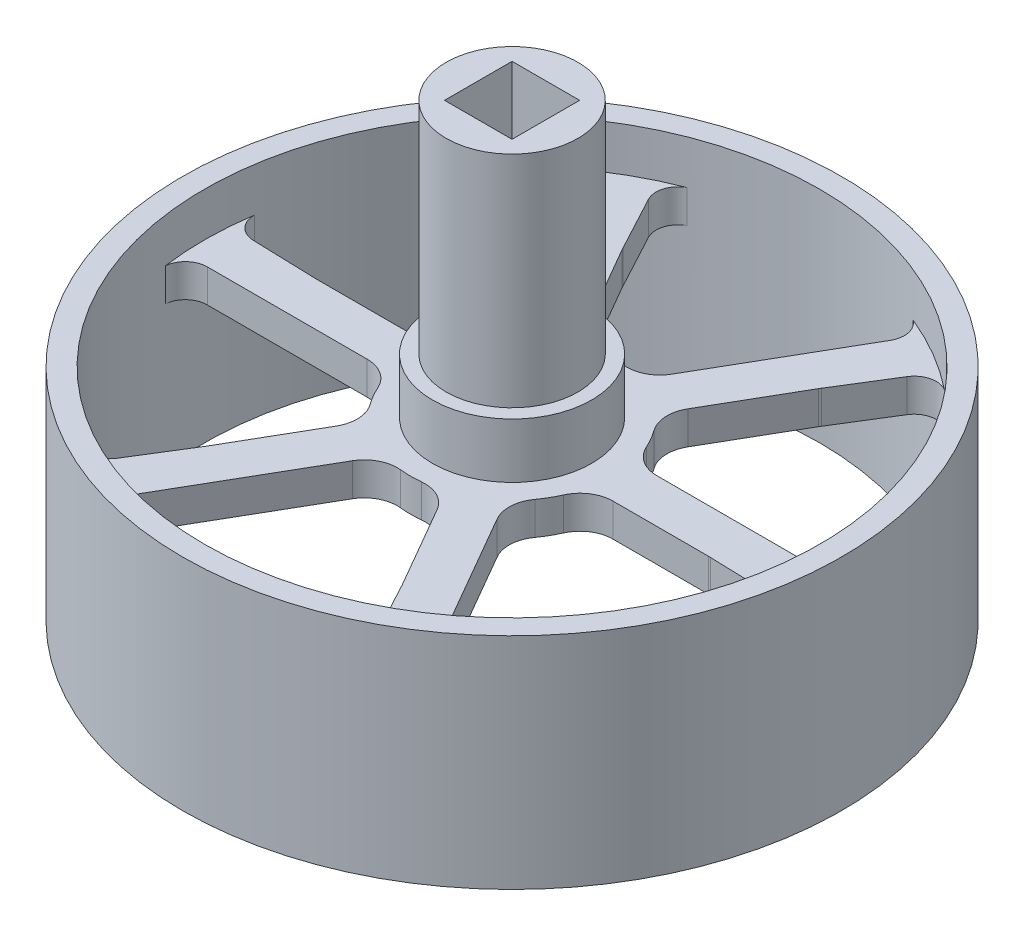
SolidWorks part; units mm, degrees
ref_plane "Front Plane" through (0, 0, 0) normal (0, 0, 1) x (1, 0, 0)
ref_plane "Top Plane" through (0, 0, 0) normal (0, 1, 0) x (1, 0, 0)
ref_plane "Right Plane" through (0, 0, 0) normal (1, 0, 0) x (0, 0, -1)
sketch "Sketch1" plane through (0, 0, 0) normal (0, 1, 0) x (1, 0, 0)
  circle A0 centre (0, 0) radius 30
  circle A1 centre (0, 0) radius 28
  dimension "D1" = 60
  dimension "D2" = 2
extrude "Boss-Extrude1" add sketch "Sketch1" along normal mid plane 20
sketch "Sketch2" plane through (0, 0, 0) normal (0, 1, 0) x (1, 0, 0)
  circle A0 centre (0, 0) radius 28
  circle A1 centre (0, 0) radius 28 construction
extrude "Boss-Extrude2" add sketch "Sketch2" along normal blind 3 from offset 3
sketch "Sketch3" plane through (0, 3, 0) normal (0, -1, 0) x (1, 0, 0)
  circle A0 centre (0, 0) radius 7.25
  dimension "D1" = 14.5
extrude "Boss-Extrude3" add sketch "Sketch3" against normal blind 5 from surface at -3 starting at face at (0, 6, 28)
sketch "Sketch4" plane through (0, 11, 0) normal (0, 1, 0) x (-1, 0, 0)
  circle A0 centre (0, 0) radius 6
  dimension "D1" = 12
extrude "Boss-Extrude4" add sketch "Sketch4" along normal blind 20
sketch "Sketch6" plane through (0, 3, 0) normal (0, -1, 0) x (1, 0, 0)
  line L0 (-3.625, 6.2787) -> (-12.75, 22.0836) construction
  line L1 (3.625, 6.2787) -> (12.75, 22.0836) construction
  line L2 (0, 7.25) -> (0, 4.04) construction
  line L3 (-3.625, 6.2787) -> (0, 0) construction
  line L4 (-3.8595, 10.6849) -> (-8.2084, 18.2174)
  line L5 (3.8595, 10.6849) -> (8.2084, 18.2174)
  line L6 (-2.7835, 8.8212) -> (-9.9753, 21.2778) construction
  line L7 (2.7835, 8.8212) -> (9.9753, 21.2778) construction
  line L8 (7.3236, 8.6849) -> (11.6725, 16.2174)
  line L9 (11.1831, 2) -> (19.8809, 2)
  line L10 (11.1831, -2) -> (19.8809, -2)
  line L11 (7.3236, -8.6849) -> (11.6725, -16.2174)
  line L12 (3.8595, -10.6849) -> (8.2084, -18.2174)
  line L13 (-3.8595, -10.6849) -> (-8.2084, -18.2174)
  line L14 (-7.3236, -8.6849) -> (-11.6725, -16.2174)
  line L15 (-11.1831, -2) -> (-19.8809, -2)
  line L16 (-11.1831, 2) -> (-19.8809, 2)
  line L17 (-7.3236, 8.6849) -> (-11.6725, 16.2174)
  circle A0 centre (0, 0) radius 7.25 construction
  circle A1 centre (0, 0) radius 28
  arc A3 (3.625, 6.2787) -> (-3.625, 6.2787) centre (0, 0) ccw construction
  circle A4 centre (0, 0) radius 7.25 construction
  arc A5 (6.4313, 22.6028) -> (-6.4313, 22.6028) centre (0, 0) ccw
  arc A6 (0.9525, 9.2008) -> (-0.9525, 9.2008) centre (0, 0) ccw
  arc A7 (2.7835, 8.8212) -> (-2.7835, 8.8212) centre (0, 0) ccw construction
  arc A8 (-3.8595, 10.6849) -> (-0.9525, 9.2008) centre (-1.2614, 12.1849) ccw
  arc A9 (0.9525, 9.2008) -> (3.8595, 10.6849) centre (1.2614, 12.1849) ccw
  arc A10 (9.9753, 21.2778) -> (-9.9753, 21.2778) centre (0, 0) ccw construction
  arc A11 (6.4313, 22.6028) -> (8.2084, 18.2174) centre (5.6103, 19.7174) cw
  arc A12 (-6.4313, 22.6028) -> (-8.2084, 18.2174) centre (-5.6103, 19.7174) ccw
  arc A13 (22.7903, 5.7317) -> (16.359, 16.8711) centre (0, 0) ccw
  arc A14 (16.359, 16.8711) -> (11.6725, 16.2174) centre (14.2706, 14.7174) ccw
  arc A15 (22.7903, 5.7317) -> (19.8809, 2) centre (19.8809, 5) cw
  arc A16 (7.3236, 8.6849) -> (7.4919, 5.4253) centre (9.9217, 7.1849) ccw
  arc A17 (8.4444, 3.7755) -> (7.4919, 5.4253) centre (0, 0) ccw
  arc A18 (8.4444, 3.7755) -> (11.1831, 2) centre (11.1831, 5) ccw
  arc A19 (16.359, -16.8711) -> (22.7903, -5.7317) centre (0, 0) ccw
  arc A20 (22.7903, -5.7317) -> (19.8809, -2) centre (19.8809, -5) ccw
  arc A21 (16.359, -16.8711) -> (11.6725, -16.2174) centre (14.2706, -14.7174) cw
  arc A22 (11.1831, -2) -> (8.4444, -3.7755) centre (11.1831, -5) ccw
  arc A23 (7.4919, -5.4253) -> (8.4444, -3.7755) centre (0, 0) ccw
  arc A24 (7.4919, -5.4253) -> (7.3236, -8.6849) centre (9.9217, -7.1849) ccw
  arc A25 (-6.4313, -22.6028) -> (6.4313, -22.6028) centre (0, 0) ccw
  arc A26 (6.4313, -22.6028) -> (8.2084, -18.2174) centre (5.6103, -19.7174) ccw
  arc A27 (-6.4313, -22.6028) -> (-8.2084, -18.2174) centre (-5.6103, -19.7174) cw
  arc A28 (3.8595, -10.6849) -> (0.9525, -9.2008) centre (1.2614, -12.1849) ccw
  arc A29 (-0.9525, -9.2008) -> (0.9525, -9.2008) centre (0, 0) ccw
  arc A30 (-0.9525, -9.2008) -> (-3.8595, -10.6849) centre (-1.2614, -12.1849) ccw
  arc A31 (-22.7903, -5.7317) -> (-16.359, -16.8711) centre (0, 0) ccw
  arc A32 (-16.359, -16.8711) -> (-11.6725, -16.2174) centre (-14.2706, -14.7174) ccw
  arc A33 (-22.7903, -5.7317) -> (-19.8809, -2) centre (-19.8809, -5) cw
  arc A34 (-7.3236, -8.6849) -> (-7.4919, -5.4253) centre (-9.9217, -7.1849) ccw
  arc A35 (-8.4444, -3.7755) -> (-7.4919, -5.4253) centre (0, 0) ccw
  arc A36 (-8.4444, -3.7755) -> (-11.1831, -2) centre (-11.1831, -5) ccw
  arc A37 (-16.359, 16.8711) -> (-22.7903, 5.7317) centre (0, 0) ccw
  arc A38 (-22.7903, 5.7317) -> (-19.8809, 2) centre (-19.8809, 5) ccw
  arc A39 (-16.359, 16.8711) -> (-11.6725, 16.2174) centre (-14.2706, 14.7174) cw
  arc A40 (-11.1831, 2) -> (-8.4444, 3.7755) centre (-11.1831, 5) ccw
  arc A41 (-7.4919, 5.4253) -> (-8.4444, 3.7755) centre (0, 0) ccw
  arc A42 (-7.4919, 5.4253) -> (-7.3236, 8.6849) centre (-9.9217, 7.1849) ccw
  arc A44 (12.75, 22.0836) -> (-12.75, 22.0836) centre (0, 0) ccw construction
  circle A46 centre (0, 0) radius 28
  point P92 (0, 0)
  dimension "D3" = 2
  dimension "D4" = 3
  dimension "D2" = 60
  dimension "D1" = 0
  dimension "D5" = 6
extrude "Cut-Extrude2" cut sketch "Sketch6" against normal blind 9 contours A41 A42 L17 A39 A37 A38 L16 A40 | A5 A12 L4 A8 A6 A9 L5 A11 | A17 A18 L9 A15 A13 A14 L8 A16 | A23 A24 L11 A21 A19 A20 L10 A22 | A29 A30 L13 A27 A25 A26 L12 A28 | A35 A36 L15 A33 A31 A32 L14 A34
sketch "Sketch7" plane through (0, 3, 0) normal (0, -1, 0) x (1, 0, 0)
  line L0 (8.2084, 18.2174) -> (10.9792, 23.3843)
  line L1 (-8.2084, 18.2174) -> (-11.1399, 23.2949)
  line L2 (-8.2084, 18.2174) -> (-3.8595, 10.6849) construction
  line L3 (11.6725, 16.2174) -> (14.604, 21.2949)
  line L4 (19.8809, 2) -> (25.741, 2.1839)
  line L5 (19.8809, -2) -> (25.7439, -2)
  line L6 (11.6725, -16.2174) -> (14.7618, -21.2004)
  line L7 (8.2084, -18.2174) -> (11.1399, -23.2949)
  line L8 (-8.2084, -18.2174) -> (-10.9792, -23.3843)
  line L9 (-11.6725, -16.2174) -> (-14.604, -21.2949)
  line L10 (-19.8809, -2) -> (-25.741, -2.1839)
  line L11 (-19.8809, 2) -> (-25.7439, 2)
  line L12 (-11.6725, 16.2174) -> (-14.7618, 21.2004)
  circle A0 centre (0, 0) radius 28 construction
  circle A1 centre (0, 0) radius 28 construction
  arc A2 (-6.4313, 22.6028) -> (-8.2084, 18.2174) centre (-5.6103, 19.7174) ccw construction
  circle A3 centre (0, 0) radius 28
  arc A5 (8.2084, 18.2174) -> (6.4313, 22.6028) centre (5.6103, 19.7174) ccw construction
  arc A6 (6.4313, 22.6028) -> (-6.4313, 22.6028) centre (0, 0) ccw construction
  arc A7 (-6.4313, 22.6028) -> (-8.2084, 18.2174) centre (-5.6103, 19.7174) ccw
  arc A8 (8.2084, 18.2174) -> (6.4313, 22.6028) centre (5.6103, 19.7174) ccw
  arc A9 (6.4313, 22.6028) -> (-6.4313, 22.6028) centre (0, 0) ccw
  arc A10 (10.9792, 23.3843) -> (9.6683, 26.2778) centre (9.2167, 24.3295) ccw
  arc A11 (-11.1399, 23.2949) -> (-9.6683, 26.2778) centre (-9.4078, 24.2949) cw
  arc A12 (19.8809, 2) -> (22.7903, 5.7317) centre (19.8809, 5) ccw
  arc A13 (22.7903, 5.7317) -> (16.359, 16.8711) centre (0, 0) ccw
  arc A14 (16.359, 16.8711) -> (11.6725, 16.2174) centre (14.2706, 14.7174) ccw
  arc A15 (14.604, 21.2949) -> (17.9231, 21.5119) centre (16.336, 20.2949) cw
  arc A16 (27.5914, 4.766) -> (17.9231, 21.5119) centre (0, 0) ccw
  arc A17 (25.741, 2.1839) -> (27.5914, 4.766) centre (25.6783, 4.1829) ccw
  arc A18 (11.6725, -16.2174) -> (16.359, -16.8711) centre (14.2706, -14.7174) ccw
  arc A19 (16.359, -16.8711) -> (22.7903, -5.7317) centre (0, 0) ccw
  arc A20 (22.7903, -5.7317) -> (19.8809, -2) centre (19.8809, -5) ccw
  arc A21 (25.7439, -2) -> (27.5914, -4.766) centre (25.7439, -4) cw
  arc A22 (17.9231, -21.5119) -> (27.5914, -4.766) centre (0, 0) ccw
  arc A23 (14.7618, -21.2004) -> (17.9231, -21.5119) centre (16.4616, -20.1466) ccw
  arc A24 (-8.2084, -18.2174) -> (-6.4313, -22.6028) centre (-5.6103, -19.7174) ccw
  arc A25 (-6.4313, -22.6028) -> (6.4313, -22.6028) centre (0, 0) ccw
  arc A26 (6.4313, -22.6028) -> (8.2084, -18.2174) centre (5.6103, -19.7174) ccw
  arc A27 (11.1399, -23.2949) -> (9.6683, -26.2778) centre (9.4078, -24.2949) cw
  arc A28 (-9.6683, -26.2778) -> (9.6683, -26.2778) centre (0, 0) ccw
  arc A29 (-10.9792, -23.3843) -> (-9.6683, -26.2778) centre (-9.2167, -24.3295) ccw
  arc A30 (-19.8809, -2) -> (-22.7903, -5.7317) centre (-19.8809, -5) ccw
  arc A31 (-22.7903, -5.7317) -> (-16.359, -16.8711) centre (0, 0) ccw
  arc A32 (-16.359, -16.8711) -> (-11.6725, -16.2174) centre (-14.2706, -14.7174) ccw
  arc A33 (-14.604, -21.2949) -> (-17.9231, -21.5119) centre (-16.336, -20.2949) cw
  arc A34 (-27.5914, -4.766) -> (-17.9231, -21.5119) centre (0, 0) ccw
  arc A35 (-25.741, -2.1839) -> (-27.5914, -4.766) centre (-25.6783, -4.1829) ccw
  arc A36 (-11.6725, 16.2174) -> (-16.359, 16.8711) centre (-14.2706, 14.7174) ccw
  arc A37 (-16.359, 16.8711) -> (-22.7903, 5.7317) centre (0, 0) ccw
  arc A38 (-22.7903, 5.7317) -> (-19.8809, 2) centre (-19.8809, 5) ccw
  arc A39 (-25.7439, 2) -> (-27.5914, 4.766) centre (-25.7439, 4) cw
  arc A40 (-17.9231, 21.5119) -> (-27.5914, 4.766) centre (0, 0) ccw
  arc A41 (-14.7618, 21.2004) -> (-17.9231, 21.5119) centre (-16.4616, 20.1466) ccw
  circle A44 centre (0, 0) radius 28
  point P16 (12.055, 25.2721)
  point P22 (-12.055, 25.2721)
  point P85 (0, 0)
  circle M18 centre (0, 0) radius 28
  arc M22 (-8.2084, 18.2174) -> (-6.4313, 22.6028) centre (-5.6103, 19.7174) cw
  arc M23 (-6.4313, 22.6028) -> (6.4313, 22.6028) centre (0, 0) cw
  arc M24 (6.4313, 22.6028) -> (8.2084, 18.2174) centre (5.6103, 19.7174) cw
  arc M30 (-19.8809, 2) -> (-22.7903, 5.7317) centre (-19.8809, 5) cw
  arc M31 (-22.7903, 5.7317) -> (-16.359, 16.8711) centre (0, 0) cw
  arc M32 (-16.359, 16.8711) -> (-11.6725, 16.2174) centre (-14.2706, 14.7174) cw
  arc M38 (11.6725, 16.2174) -> (16.359, 16.8711) centre (14.2706, 14.7174) cw
  arc M39 (16.359, 16.8711) -> (22.7903, 5.7317) centre (0, 0) cw
  arc M40 (22.7903, 5.7317) -> (19.8809, 2) centre (19.8809, 5) cw
  arc M46 (19.8809, -2) -> (22.7903, -5.7317) centre (19.8809, -5) cw
  arc M47 (22.7903, -5.7317) -> (16.359, -16.8711) centre (0, 0) cw
  arc M48 (16.359, -16.8711) -> (11.6725, -16.2174) centre (14.2706, -14.7174) cw
  arc M54 (-11.6725, -16.2174) -> (-16.359, -16.8711) centre (-14.2706, -14.7174) cw
  arc M55 (-16.359, -16.8711) -> (-22.7903, -5.7317) centre (0, 0) cw
  arc M56 (-22.7903, -5.7317) -> (-19.8809, -2) centre (-19.8809, -5) cw
  arc M62 (8.2084, -18.2174) -> (6.4313, -22.6028) centre (5.6103, -19.7174) cw
  arc M63 (6.4313, -22.6028) -> (-6.4313, -22.6028) centre (0, 0) cw
  arc M64 (-6.4313, -22.6028) -> (-8.2084, -18.2174) centre (-5.6103, -19.7174) cw
  dimension "D2" = 2
  dimension "D1" = 0
  dimension "D3" = 6
extrude "Cut-Extrude3" cut sketch "Sketch7" against normal blind 10 contours L12 A41 A39 L11 M18 M30 M31 M32 | A11 L1 L0 A10 M22 M23 M24 M18 | L4 A17 A15 L3 M18 M38 M39 M40 | L6 A23 A21 L5 M18 M46 M47 M48 | L8 A29 A27 L7 M18 M62 M63 M64 | L10 A35 A33 L9 M18 M54 M55 M56
sketch "Sketch8" plane through (0, 31, 0) normal (0, 1, 0) x (-1, 0, 0)
  line L1 (-3.0744, -3.0744) -> (3.0744, -3.0744)
  line L2 (-3.0744, -3.0744) -> (-3.0744, 3.0744)
  line L3 (-3.0744, 3.0744) -> (3.0744, 3.0744)
  line L4 (3.0744, -3.0744) -> (3.0744, 3.0744)
  line L5 (-3.0744, -3.0744) -> (3.0744, 3.0744) construction
  line L6 (-3.0744, 3.0744) -> (3.0744, -3.0744) construction
  point P0 (0, 0)
  dimension "D1" = 6.1488
extrude "Cut-Extrude4" cut sketch "Sketch8" against normal blind 20
